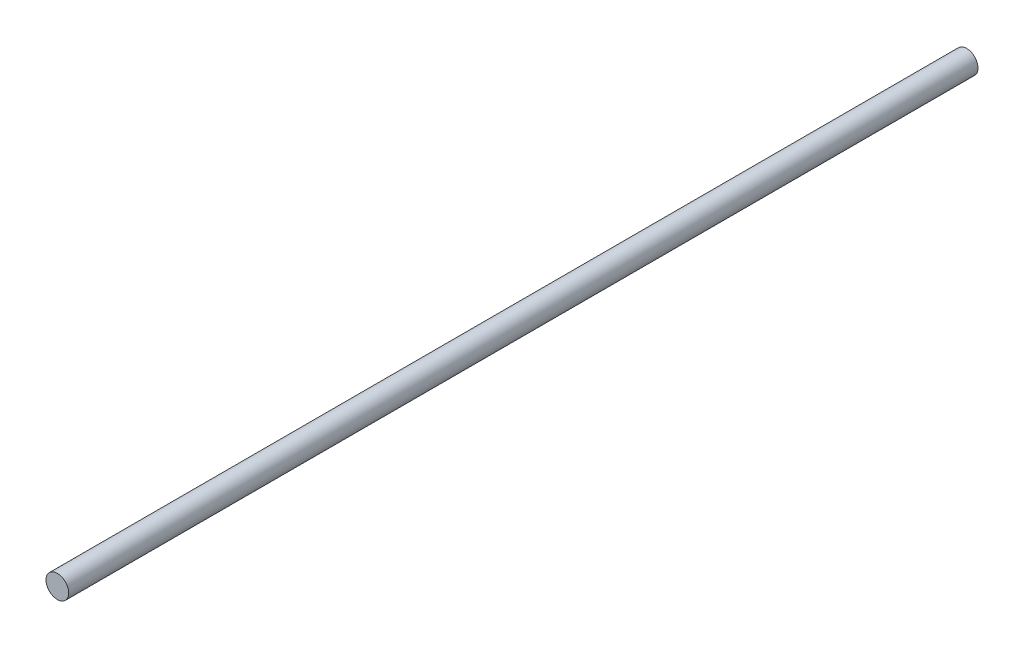
SolidWorks part; units mm, degrees
ref_plane "Front Plane" through (0, 0, 0) normal (0, 0, 1) x (1, 0, 0)
ref_plane "Top Plane" through (0, 0, 0) normal (0, 1, 0) x (1, 0, 0)
ref_plane "Right Plane" through (0, 0, 0) normal (1, 0, 0) x (0, 0, -1)
sketch "Sketch1" plane through (0, 0, 0) normal (0, 0, 1) x (1, 0, 0)
  circle A0 centre (0, 0) radius 6.35
  dimension "D1" = 12.7
extrude "Boss-Extrude1" add sketch "Sketch1" along normal mid plane 508
